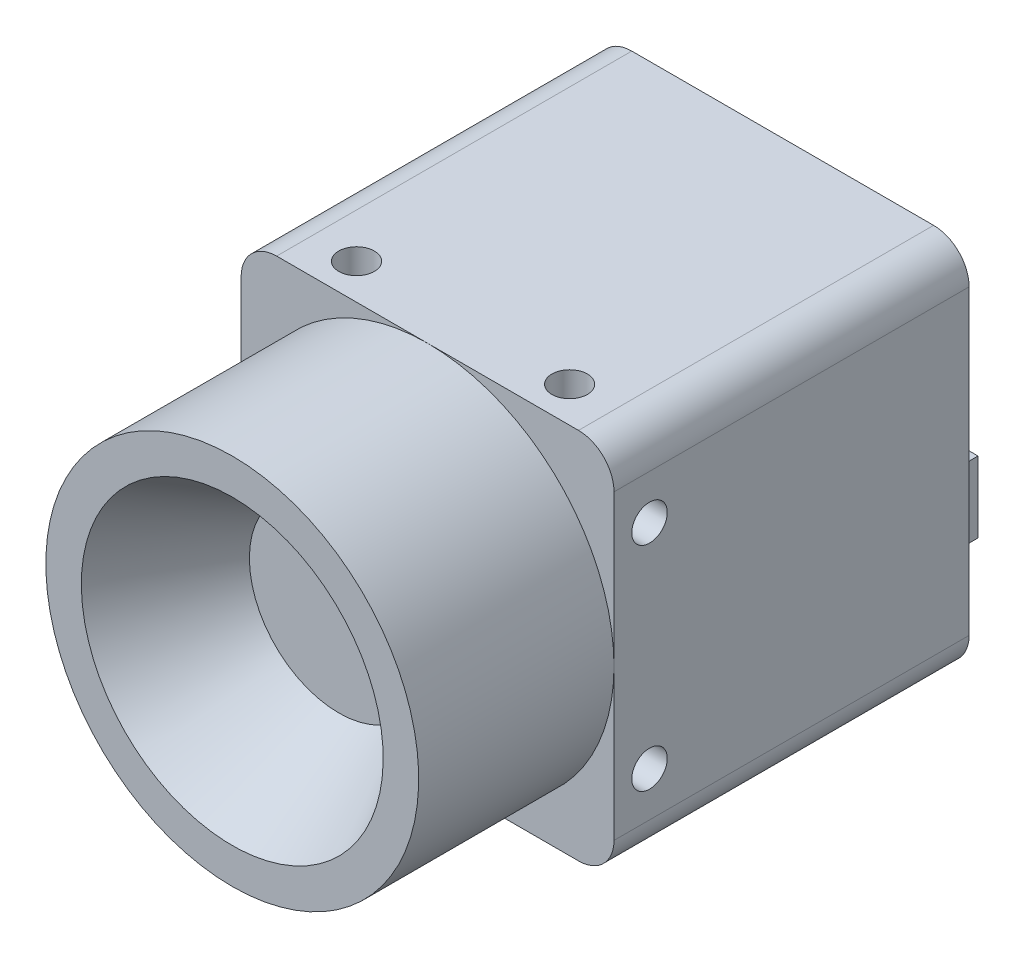
SolidWorks part; units mm, degrees
ref_plane "Front Plane" through (0, 0, 0) normal (0, 0, 1) x (1, 0, 0)
ref_plane "Top Plane" through (0, 0, 0) normal (0, 1, 0) x (1, 0, 0)
ref_plane "Right Plane" through (0, 0, 0) normal (1, 0, 0) x (0, 0, -1)
sketch "Sketch1" plane through (0, 0, 0) normal (0, 0, 1) x (1, 0, 0)
  line L1 (-8.5, -10.5) -> (8.5, -10.5)
  line L2 (-10.5, -8.5) -> (-10.5, 8.5)
  line L3 (-8.5, 10.5) -> (8.5, 10.5)
  line L4 (10.5, -8.5) -> (10.5, 8.5)
  line L5 (-10.5, -10.5) -> (10.5, 10.5) construction
  line L6 (-10.5, 10.5) -> (10.5, -10.5) construction
  arc A0 (-8.5, -10.5) -> (-10.5, -8.5) centre (-8.5, -8.5) cw
  arc A1 (8.5, -10.5) -> (10.5, -8.5) centre (8.5, -8.5) ccw
  arc A2 (8.5, 10.5) -> (10.5, 8.5) centre (8.5, 8.5) cw
  arc A3 (-10.5, 8.5) -> (-8.5, 10.5) centre (-8.5, 8.5) cw
  point P0 (0, 0)
  dimension "D3" = 2
  dimension "D1" = 21
  dimension "D2" = 21
extrude "Boss-Extrude1" add sketch "Sketch1" along normal blind 20
sketch "Sketch3" plane through (0, 0, 0) normal (1, 0, 0) x (0, 0, -1)
  line L0 (-20, 10.5) -> (-20, 0)
  line L1 (-20, -8.5) -> (-20, 8.5) construction
  line L2 (-20, 0) -> (-25, 0)
  line L3 (-25, 0) -> (-25, 5.0359)
  line L4 (-25, 5.0359) -> (-31, 8.5)
  line L5 (-31, 8.5) -> (-31, 10.5)
  line L6 (-31, 10.5) -> (-20, 10.5)
  point P5 (-28, 5.4835)
  dimension "D1" = 2
  dimension "D2" = 120
  dimension "D3" = 5
  dimension "D4" = 11
revolve "Revolve1" add sketch "Sketch3" angle 360 about L2
sketch "Sketch4" plane through (0, 0, 0) normal (0, 0, -1) x (-1, 0, 0)
  line L0 (8.5, -10.5) -> (-8.5, -10.5) construction
  line L1 (-5, -5.5) -> (5, -5.5)
  line L2 (-5, -5.5) -> (-5, -9.5)
  line L3 (-5, -9.5) -> (5, -9.5)
  line L4 (5, -5.5) -> (5, -9.5)
  point P4 (0, -5.5)
  dimension "D1" = 4
  dimension "D2" = 10
  dimension "D3" = 1
extrude "Boss-Extrude2" add sketch "Sketch4" along normal blind 6
sketch "Sketch5" plane through (-10.5, 0, 0) normal (-1, 0, 0) x (0, 0, 1)
  line L0 (20, 0) -> (20, 10.5) construction
  line L2 (18, -6) -> (18, 6) construction
  circle A0 centre (18, 6) radius 1
  circle A1 centre (18, -6) radius 1
  point P4 (18, 0)
  dimension "D1" = 2
  dimension "D2" = 2
  dimension "D3" = 12
extrude "Cut-Extrude1" cut sketch "Sketch5" against normal blind 3
pattern_circular "CirPattern1" count 4 over 360 about axis through (0, 0, 0) along (0, 0, 1) of "Cut-Extrude1"
